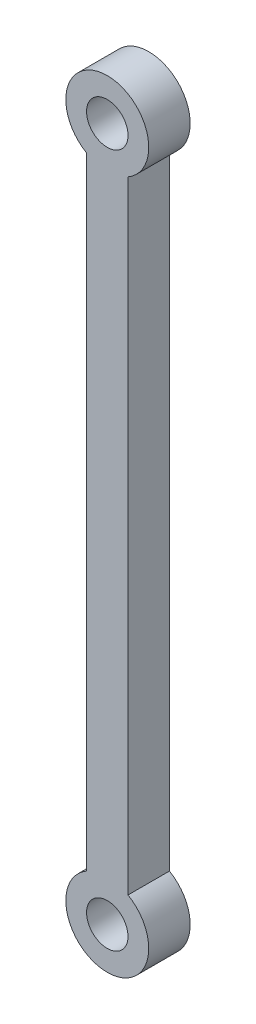
SolidWorks part; units mm, degrees
ref_plane "Front Plane" through (0, 0, 0) normal (0, 0, 1) x (1, 0, 0)
ref_plane "Top Plane" through (0, 0, 0) normal (0, 1, 0) x (1, 0, 0)
ref_plane "Right Plane" through (0, 0, 0) normal (1, 0, 0) x (0, 0, -1)
sketch "Sketch1" plane through (0, 0, 0) normal (0, 0, 1) x (1, 0, 0)
  line L0 (0, 0) -> (0, 30)
  line L2 (2, 30) -> (2, 0)
  arc A0 (0, 30) -> (2, 30) centre (1, 31.7321) cw
  arc A1 (0, 0) -> (2, 0) centre (1, -1.7321) ccw
  circle A2 centre (1, 31.7321) radius 1
  circle A3 centre (1, -1.7321) radius 1
  dimension "D1" = 2
  dimension "D3" = 2
  dimension "D4" = 2
  dimension "D2" = 30
extrude "Boss-Extrude1" add sketch "Sketch1" along normal blind 2
